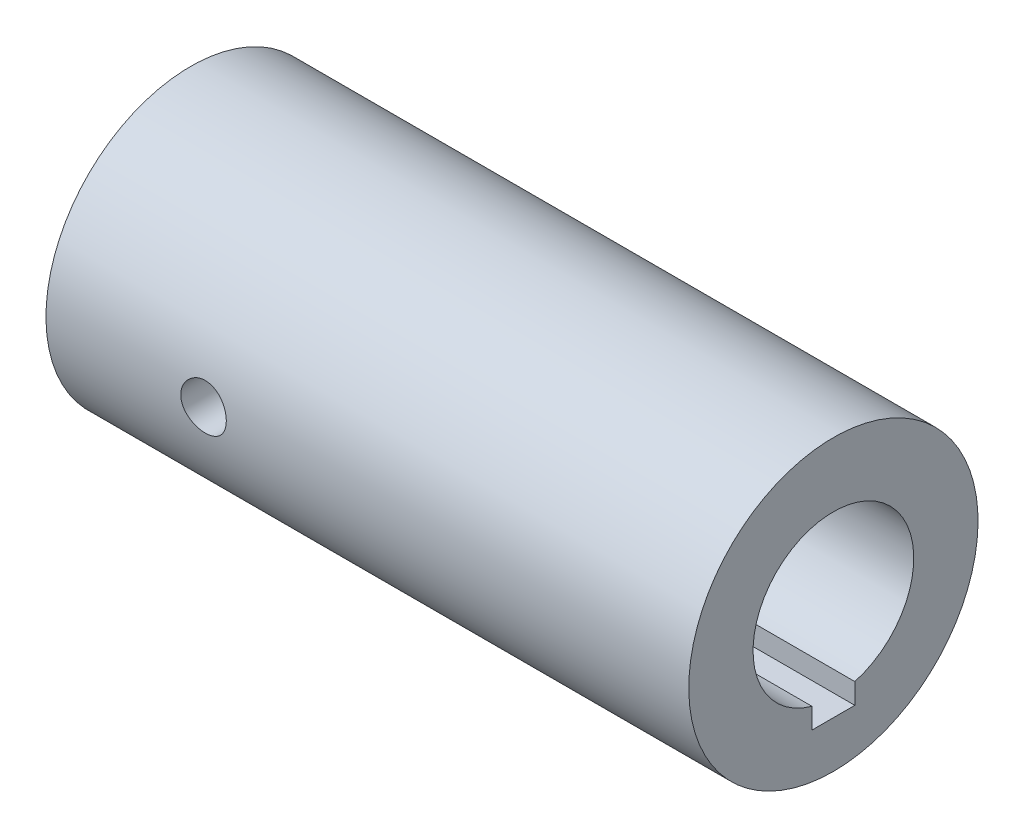
SolidWorks part; units mm, degrees
ref_plane "Ön Düzlem" through (0, 0, 0) normal (0, 0, 1) x (1, 0, 0)
ref_plane "Üst Düzlem" through (0, 0, 0) normal (0, 1, 0) x (1, 0, 0)
ref_plane "Sağ Düzlem" through (0, 0, 0) normal (1, 0, 0) x (0, 0, -1)
sketch "Çizim1" plane through (0, 0, 0) normal (0, 0, 1) x (1, 0, 0)
  line L0 (-60, 0) -> (60, 0) construction
  line L2 (-60, 15) -> (60, 15)
  line L3 (-60, 15) -> (-60, 27)
  line L4 (-60, 27) -> (60, 27)
  line L5 (60, 15) -> (60, 27)
  point P2 (0, 0)
  dimension "D1" = 120
  dimension "D2" = 15
  dimension "D3" = 12
revolve "Döndür1" add sketch "Çizim1" angle 360 about L0
sketch "Çizim2" plane through (0, 0, 0) normal (0, 1, 0) x (1, 0, 0)
  line L0 (-60, 27) -> (-60, -27) construction
  line L1 (-60, 4) -> (60, 4)
  line L2 (-60, 4) -> (-60, -4)
  line L3 (-60, -4) -> (60, -4)
  line L4 (60, 4) -> (60, -4)
  line L5 (60, -27) -> (60, 27) construction
  point P8 (-60, 0)
  dimension "D1" = 8
extrude "Kes-Ekstrüzyon1" cut sketch "Çizim2" against normal blind 18.3
ref_plane "Düzlem1" through (0, 0, -30) normal (0, 0, 1) x (1, 0, 0)
hole_wizard "M10 Dişli Delik4" positions "Çizim6" profile "Çizim7" tap size "M10" standard "ISO"
sketch "Çizim6" plane through (0, 0, -30) normal (0, 0, 1) x (1, 0, 0)
  point P0 (-30.5849, 0)
sketch "Çizim7" plane through (-30.5849, 0, -30) normal (1, 0, 0) x (0, 1, 0)
  line L0 (0, 0) -> (0, 37.1137)
  line L1 (0, 37.1137) -> (4.25, 34.56)
  line L2 (4.25, 34.56) -> (4.25, 0.775)
  line L3 (4.25, 0.775) -> (5.025, 0)
  line L5 (5.025, 0) -> (0, 0)
  line L6 (-4.25, 0.775) -> (-5.025, 0) construction
  line L10 (0, 37.1137) -> (-4.25, 34.56) construction
  line L11 (0, -6.35) -> (0, 107.95) construction
  dimension "Tap Drill Dia." = 8.5
  dimension "Tap Drill Depth" = 34.56
  dimension "Near C'Sink Dia." = 10.05
  dimension "Near C'Sink Angle" = 90
  dimension "Drill Angle" = 118
cosmetic thread "Delik Dişi1" parameters "D1"=15.6147, "D2"=10
mirror "Aynalama1" about plane through (0, 0, 0) normal (0, 0, 1) of "M10 Dişli Delik4"
cosmetic thread "Delik Dişi2"
